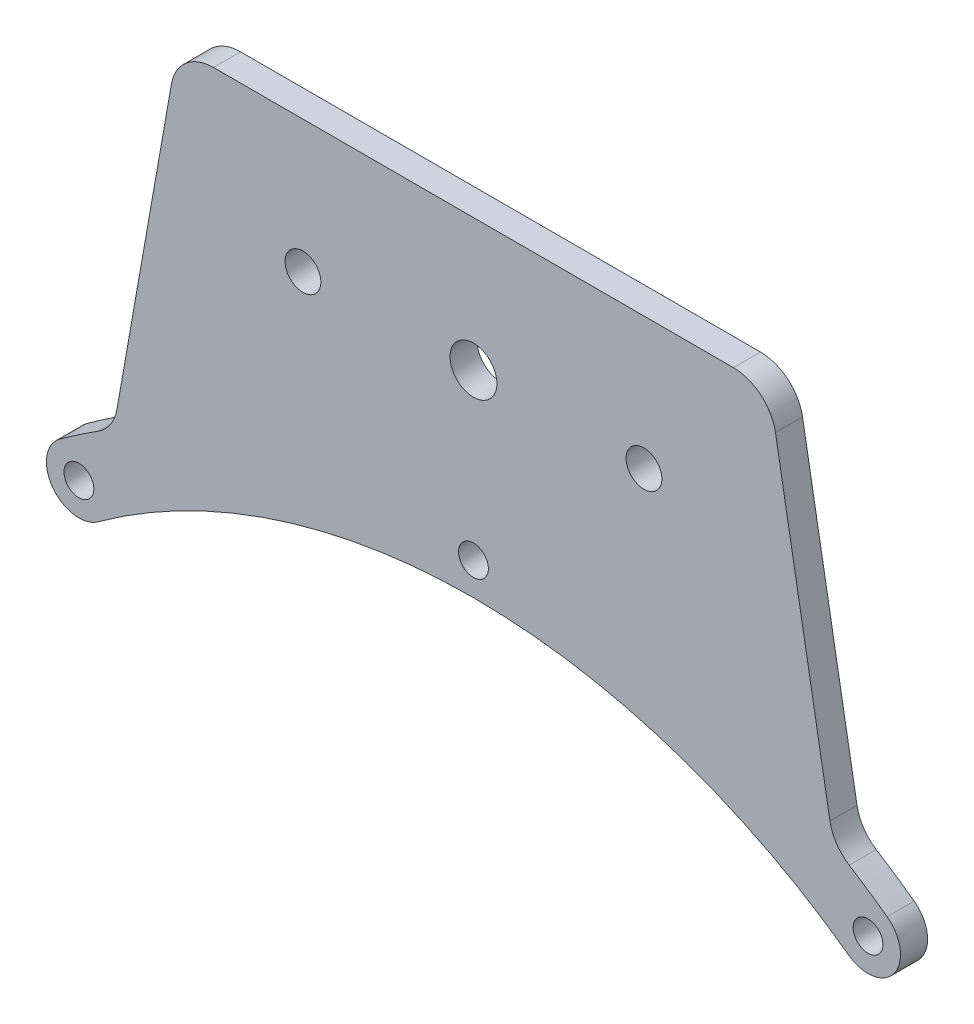
SolidWorks part; units mm, degrees
material "6061-T6 (SS)"
ref_plane "Front Plane" through (0, 0, 0) normal (0, 0, 1) x (1, 0, 0)
ref_plane "Top Plane" through (0, 0, 0) normal (0, 1, 0) x (1, 0, 0)
ref_plane "Right Plane" through (0, 0, 0) normal (1, 0, 0) x (0, 0, -1)
sketch "Sketch1" plane through (0, 0, 0) normal (0, 0, 1) x (1, 0, 0)
  line L0 (0, 0) -> (0, -78.74) construction
  line L1 (-46.2822, -15.038) -> (0, -78.74) construction
  line L2 (0, -78.74) -> (46.2822, -15.038) construction
  line L3 (0, -78.74) -> (0, -157.48) construction
  line L4 (0, 0) -> (0, 19.31) construction
  line L5 (-10.5, 29.81) -> (10.5, 8.81) construction
  line L6 (-10.5, 29.31) -> (-10.5, 9.31) construction
  line L7 (10.5, 29.81) -> (-10.5, 8.81) construction
  line L8 (-10, 8.81) -> (10, 8.81) construction
  line L9 (10.5, 9.31) -> (10.5, 29.31) construction
  line L10 (10, 29.81) -> (-10, 29.81) construction
  line L11 (-10, 29.31) -> (-10, 9.31) construction
  line L12 (-10, 9.31) -> (10, 9.31) construction
  line L13 (10, 9.31) -> (10, 29.31) construction
  line L14 (10, 29.31) -> (-10, 29.31) construction
  line L15 (0, 19.31) -> (-20, 19.31) construction
  line L16 (0, 19.31) -> (20, 19.31) construction
  line L17 (-30.5, 34.81) -> (30.5, 34.81)
  line L18 (35.424, 30.6782) -> (41.8173, -5.5795)
  line L19 (-35.424, 30.6782) -> (-41.8173, -5.5795)
  line L20 (0, 34.81) -> (0, 19.31) construction
  line L21 (-40.1616, 3.81) -> (40.1616, 3.81) construction
  line L22 (-10.5, 29.81) -> (-30.5, 29.81) construction
  line L23 (-30.5, 29.81) -> (-30.5, 8.81) construction
  line L24 (-30.5, 8.81) -> (-10.5, 8.81) construction
  circle A0 centre (0, 0) radius 1.75
  circle A1 centre (0, -78.74) radius 78.74 construction
  circle A2 centre (-46.2822, -15.038) radius 1.75
  circle A3 centre (46.2822, -15.038) radius 1.75
  circle A10 centre (0, -78.74) radius 63.5 construction
  arc A11 (-48.5217, -11.9556) -> (48.5217, -11.9556) centre (0, -78.74) ccw construction
  arc A12 (-44.0427, -18.1204) -> (44.0427, -18.1204) centre (0, -78.74) cw
  arc A13 (-48.5217, -11.9556) -> (-44.0427, -18.1204) centre (-46.2822, -15.038) ccw
  arc A14 (48.5217, -11.9556) -> (44.0427, -18.1204) centre (46.2822, -15.038) cw
  arc A15 (48.5217, -11.9556) -> (44.0719, -8.9391) centre (0, -78.74) ccw
  circle A17 centre (-20, 19.31) radius 2.1
  circle A18 centre (20, 19.31) radius 2.1
  arc A22 (-44.0719, -8.9391) -> (-48.5217, -11.9556) centre (0, -78.74) ccw
  arc A23 (42.2082, -7.7966) -> (-42.2082, -7.7966) centre (0, -78.74) ccw construction
  arc A24 (44.0719, -8.9391) -> (41.8173, -5.5795) centre (46.7413, -4.7113) cw
  arc A25 (-41.8173, -5.5795) -> (-44.0719, -8.9391) centre (-46.7413, -4.7113) cw
  arc A26 (30.5, 34.81) -> (35.424, 30.6782) centre (30.5, 29.81) cw
  arc A27 (-30.5, 34.81) -> (-35.424, 30.6782) centre (-30.5, 29.81) ccw
  arc A28 (10.5, 9.31) -> (10, 8.81) centre (10, 9.31) cw construction
  arc A29 (-10, 8.81) -> (-10.5, 9.31) centre (-10, 9.31) cw construction
  arc A30 (10.5, 29.31) -> (10, 29.81) centre (10, 29.31) ccw construction
  arc A31 (-10, 29.81) -> (-10.5, 29.31) centre (-10, 29.31) ccw construction
  circle A32 centre (0, 19.31) radius 2.75
  dimension "D1" = 3.5
  dimension "D2" = 157.48
  dimension "D4" = 165.1
  dimension "D5" = 127
  dimension "D8" = 4.2
  dimension "D9" = 5
  dimension "D11" = 5
  dimension "D13" = 0.5
  dimension "D14" = 5.5
  dimension "D3" = 36
  dimension "D6" = 20
  dimension "D7" = 0.5
  dimension "D10" = 10
  dimension "D12" = 5
extrude "Boss-Extrude1" add sketch "Sketch1" along normal mid plane 3.175
sketch "Sketch2" plane through (0, 0, 0) normal (0, 0, 1) x (1, 0, 0)
  line L1 (-35.424, 30.6782) -> (-41.8173, -5.5795) construction
  line L2 (41.8173, -5.5795) -> (35.424, 30.6782) construction
  line L3 (-31.3816, 29.81) -> (31.3816, 29.81)
  line L6 (35.424, 30.6782) -> (36.3057, 25.6782)
  line L8 (41.8173, -5.5795) -> (35.424, 30.6782)
  line L9 (30.5, 34.81) -> (-30.5, 34.81)
  line L10 (-35.424, 30.6782) -> (-41.8173, -5.5795)
  line L12 (30.5, 34.81) -> (-30.5, 34.81)
  line L13 (-35.424, 30.6782) -> (-36.3057, 25.6782)
  line L17 (10, 29.81) -> (-10, 29.81) construction
  arc A0 (-31.3816, 29.81) -> (-36.3057, 25.6782) centre (-31.3816, 24.81) ccw
  arc A1 (36.3057, 25.6782) -> (31.3816, 29.81) centre (31.3816, 24.81) ccw
  arc A9 (44.0427, -18.1204) -> (48.5217, -11.9556) centre (46.2822, -15.038) ccw
  arc A10 (48.5217, -11.9556) -> (44.0719, -8.9391) centre (0, -78.74) ccw
  arc A11 (41.8173, -5.5795) -> (44.0719, -8.9391) centre (46.7413, -4.7113) ccw
  arc A12 (35.424, 30.6782) -> (30.5, 34.81) centre (30.5, 29.81) ccw
  arc A13 (-30.5, 34.81) -> (-35.424, 30.6782) centre (-30.5, 29.81) ccw
  arc A14 (-44.0719, -8.9391) -> (-41.8173, -5.5795) centre (-46.7413, -4.7113) ccw
  arc A15 (-44.0719, -8.9391) -> (-48.5217, -11.9556) centre (0, -78.74) ccw
  arc A16 (-48.5217, -11.9556) -> (-44.0427, -18.1204) centre (-46.2822, -15.038) ccw
  arc A17 (44.0427, -18.1204) -> (-44.0427, -18.1204) centre (0, -78.74) ccw
  arc A21 (35.424, 30.6782) -> (30.5, 34.81) centre (30.5, 29.81) ccw
  arc A22 (-30.5, 34.81) -> (-35.424, 30.6782) centre (-30.5, 29.81) ccw
  dimension "D1" = 0
extrude "Cut-Extrude1" [suppressed] cut sketch "Sketch2" against normal through all both and the other way through all
